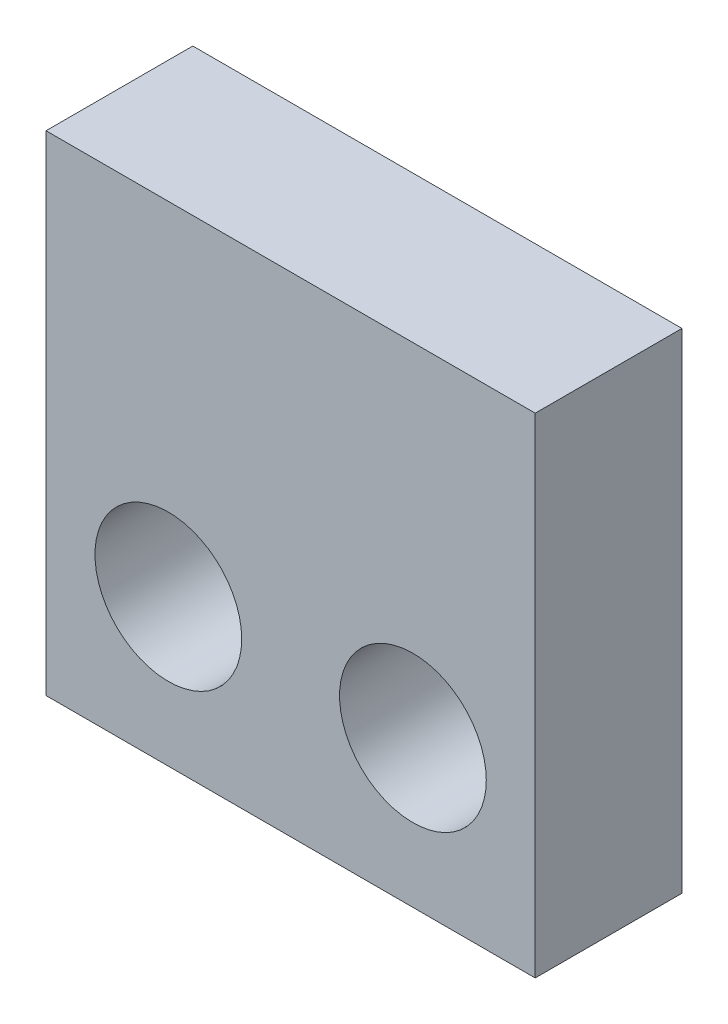
SolidWorks part; units mm, degrees
ref_plane "Front Plane" through (0, 0, 0) normal (0, 0, 1) x (1, 0, 0)
ref_plane "Top Plane" through (0, 0, 0) normal (0, 1, 0) x (1, 0, 0)
ref_plane "Right Plane" through (0, 0, 0) normal (1, 0, 0) x (0, 0, -1)
sketch "Sketch1" plane through (0, 0, 0) normal (0, 0, 1) x (1, 0, 0)
  line L1 (-2.517, 8.7075) -> (7.483, 8.7075)
  line L2 (-2.517, 8.7075) -> (-2.517, -1.2925)
  line L3 (-2.517, -1.2925) -> (7.483, -1.2925)
  line L4 (7.483, 8.7075) -> (7.483, -1.2925)
  circle A0 centre (-0.017, 1.7075) radius 1.5
  circle A1 centre (4.983, 1.7075) radius 1.5
  point P8 (0, 0)
  dimension "D3" = 3
  dimension "D4" = 3
  dimension "D1" = 10
  dimension "D2" = 10
  dimension "D5" = 3
  dimension "D6" = 2.5
  dimension "D7" = 2.5
extrude "Boss-Extrude1" add sketch "Sketch1" along normal blind 3
